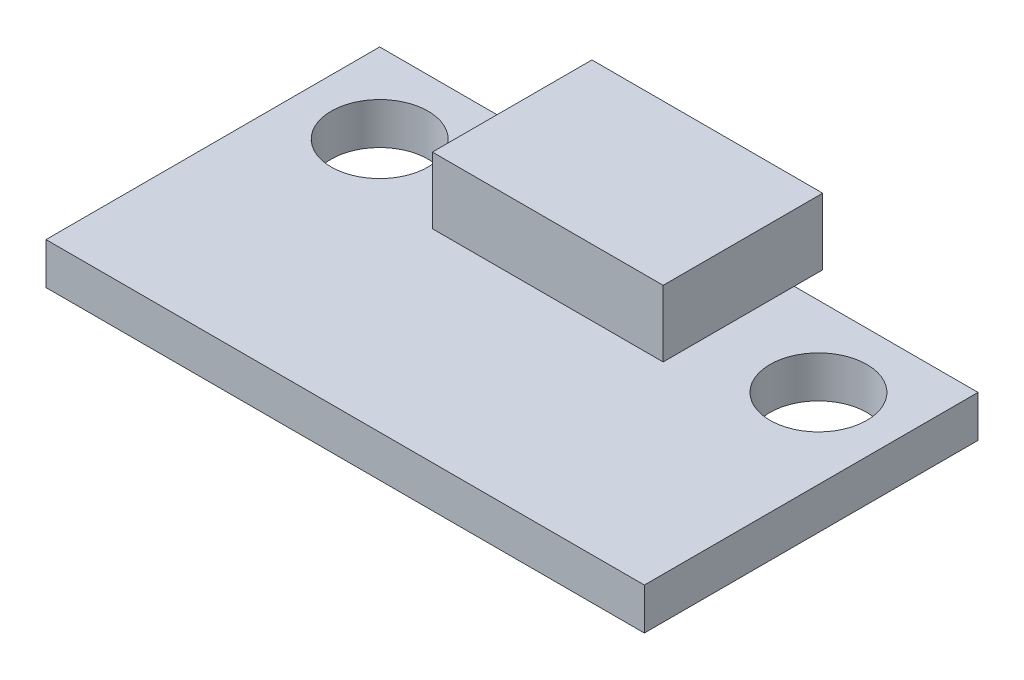
SolidWorks part; units mm, degrees
ref_plane "Front Plane" through (0, 0, 0) normal (0, 0, 1) x (1, 0, 0)
ref_plane "Top Plane" through (0, 0, 0) normal (0, 1, 0) x (1, 0, 0)
ref_plane "Right Plane" through (0, 0, 0) normal (1, 0, 0) x (0, 0, -1)
sketch "Sketch1" plane through (0, 0, 0) normal (0, 1, 0) x (1, 0, 0)
  line L0 (0, 0) -> (0, 5.855) construction
  line L1 (10.5, 5.855) -> (-10.5, 5.855)
  line L2 (10.5, 5.855) -> (10.5, -5.855)
  line L3 (10.5, -5.855) -> (-10.5, -5.855)
  line L4 (-10.5, 5.855) -> (-10.5, -5.855)
  line L5 (10.5, 5.855) -> (-10.5, -5.855) construction
  line L6 (10.5, -5.855) -> (-10.5, 5.855) construction
  circle A0 centre (-7.7, 3.055) radius 1.7
  circle A1 centre (7.7, 3.055) radius 1.7
  point P0 (0, 0)
  dimension "D3" = 3.4
  dimension "D1" = 21
  dimension "D2" = 11.71
  dimension "D4" = 2.8
  dimension "D5" = 2.8
extrude "Boss-Extrude1" add sketch "Sketch1" along normal blind 1.46
sketch "Sketch2" plane through (0, 1.46, 0) normal (0, 1, 0) x (1, 0, 0)
  line L0 (0, 0) -> (0, 5.855) construction
  line L1 (-4.05, 6.855) -> (4.05, 6.855)
  line L2 (-4.05, 6.855) -> (-4.05, 1.255)
  line L3 (-4.05, 1.255) -> (4.05, 1.255)
  line L4 (4.05, 6.855) -> (4.05, 1.255)
  line L5 (10.5, 5.855) -> (-10.5, 5.855) construction
  dimension "D1" = 5.6
  dimension "D2" = 8.1
  dimension "D3" = 1
extrude "Boss-Extrude2" add sketch "Sketch2" along normal blind 2.33
